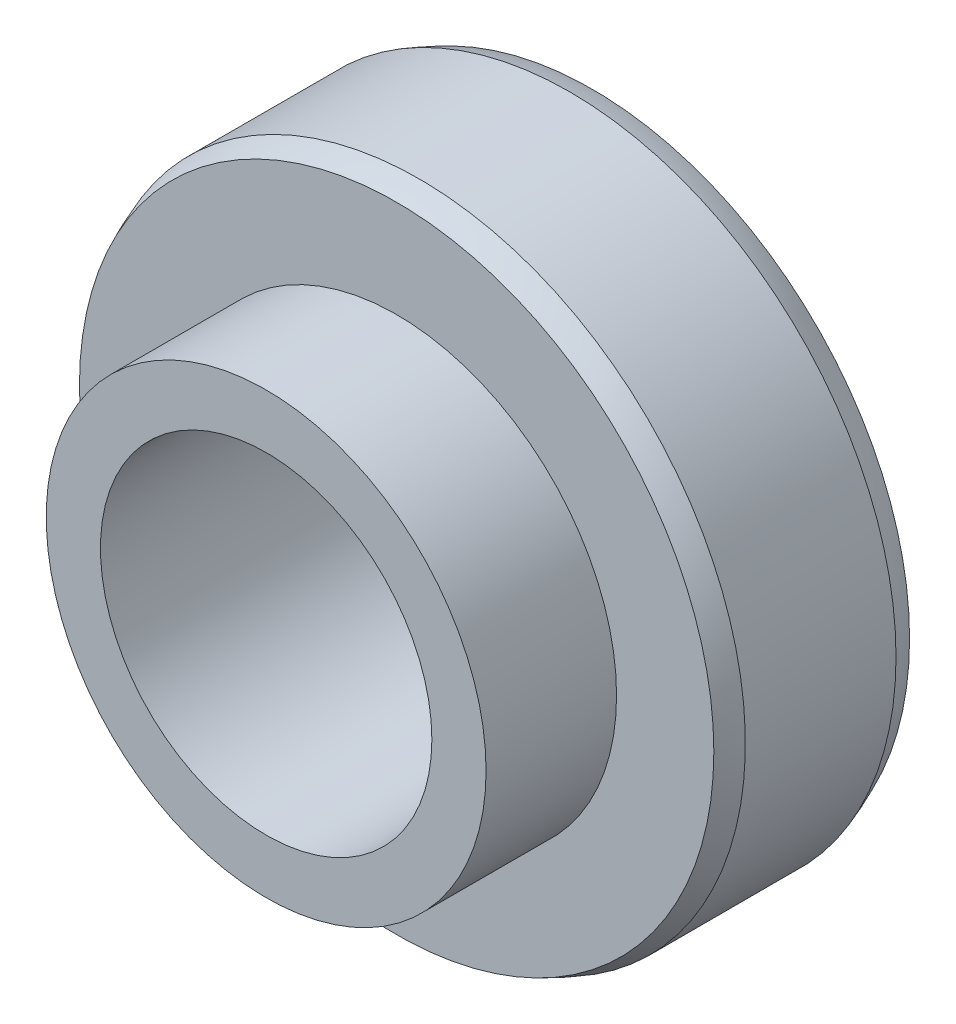
SolidWorks part; units mm, degrees
material "Chrome Stainless Steel"
ref_plane "Front Plane" through (0, 0, 0) normal (0, 0, 1) x (1, 0, 0)
ref_plane "Top Plane" through (0, 0, 0) normal (0, 1, 0) x (1, 0, 0)
ref_plane "Right Plane" through (0, 0, 0) normal (1, 0, 0) x (0, 0, -1)
sketch "Sketch1" plane through (0, 0, 0) normal (0, 0, 1) x (1, 0, 0)
  circle A0 centre (0, 0) radius 25
extrude "Boss-Extrude1" add sketch "Sketch1" along normal blind 15
sketch "Sketch2" plane through (0, 0, 15) normal (0, 0, 1) x (1, 0, 0)
  circle A0 centre (0, 0) radius 16.855
extrude "Boss-Extrude2" add sketch "Sketch2" along normal blind 10
sketch "Sketch3" plane through (0, 0, 25) normal (0, 0, 1) x (1, 0, 0)
  circle A0 centre (0, 0) radius 12.7
extrude "Cut-Extrude1" cut sketch "Sketch3" against normal blind 30
sketch "Sketch8" plane through (0, 0, 0) normal (1, 0, 0) x (0, 0, -1)
  line L0 (0, 0) -> (-29.5417, 0) construction
  line L1 (-15, 26.0113) -> (-15, 24.3113)
  line L2 (0, 26.0113) -> (-15, 26.0113)
  line L3 (0, 26.0113) -> (0, 24.3113)
  arc A0 (-15, 24.3113) -> (0, 24.3113) centre (-7.5, 8.0137) cw
revolve "Cut-Revolve13" cut sketch "Sketch8" angle 360 about L0
